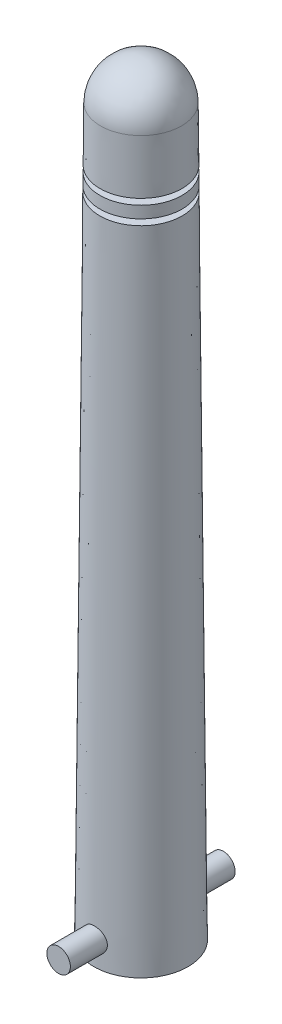
SolidWorks part; units mm, degrees
ref_plane "Plan de face" through (0, 0, 0) normal (0, 0, 1) x (1, 0, 0)
ref_plane "Plan de dessus" through (0, 0, 0) normal (0, 1, 0) x (1, 0, 0)
ref_plane "Plan de droite" through (0, 0, 0) normal (1, 0, 0) x (0, 0, -1)
sketch "Esquisse1" plane through (0, 0, 0) normal (0, 0, 1) x (1, 0, 0)
  line L0 (0, 0) -> (4, 0)
  line L1 (4, 0) -> (3.5, 55)
  line L2 (2.5, 55) -> (2.5, 55.5)
  line L3 (2.5, 55.5) -> (3.4955, 55.5)
  line L4 (3.4955, 55.5) -> (3.4864, 56.5)
  line L5 (3.4864, 56.5) -> (2.4864, 56.5)
  line L6 (2.4864, 56.5) -> (2.4864, 57)
  line L7 (2.4864, 57) -> (3.4818, 57)
  line L8 (3.4818, 57) -> (3.4401, 61.591)
  line L9 (0, 0) -> (0, 70.0582) construction
  line L10 (2.5, 55) -> (3.5, 55)
  line L11 (0, 0) -> (0, 65)
  arc A0 (3.4401, 61.591) -> (0, 65) centre (0, 61.5598) ccw
  dimension "D1" = 4
  dimension "D2" = 65
  dimension "D3" = 7
  dimension "D4" = 0.5
  dimension "D5" = 0.5
  dimension "D6" = 1
  dimension "D7" = 1
  dimension "D8" = 55
  dimension "D9" = 1
revolve "Révolution1" add sketch "Esquisse1" angle 360 about L9
sketch "Esquisse2" plane through (0, 0, 0) normal (0, 0, 1) x (1, 0, 0)
  line L0 (-4, 0) -> (4, 0) construction
  circle A0 centre (0, 2) radius 1
  dimension "D1" = 2
  dimension "D2" = 2
extrude "Extrusion1" add sketch "Esquisse2" along normal mid plane 14
